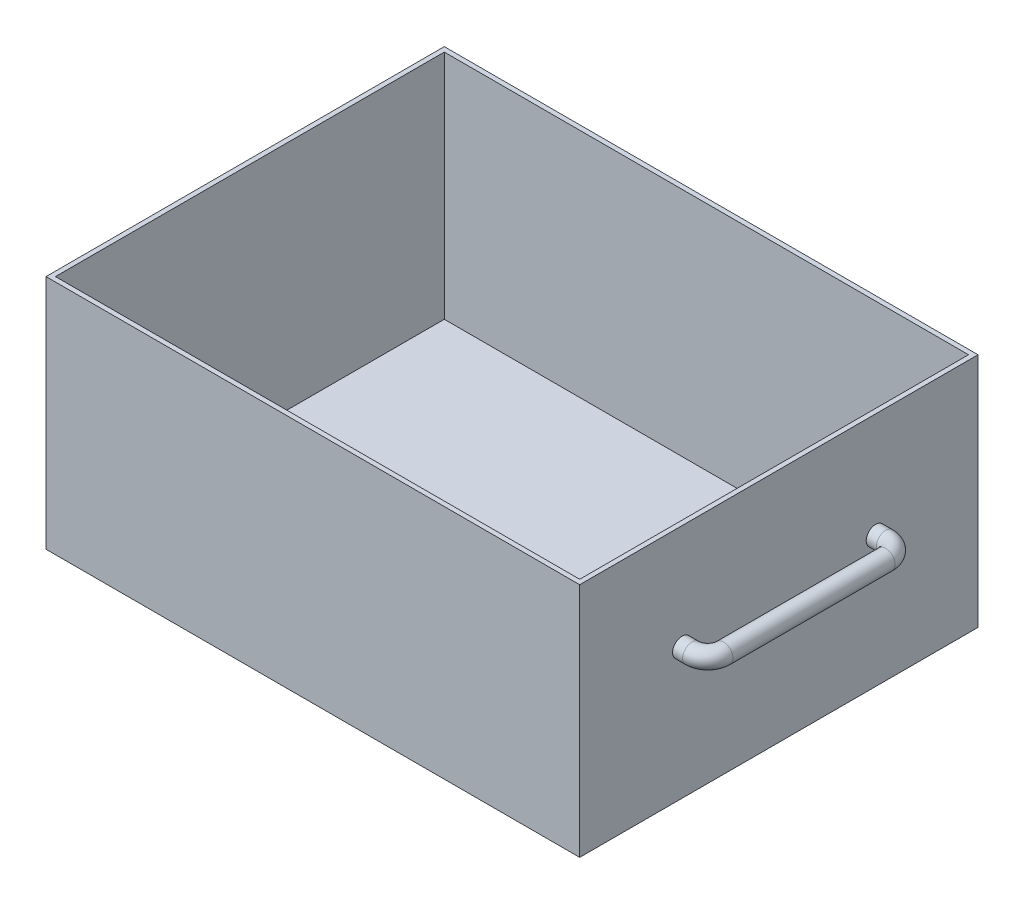
SolidWorks part; units mm, degrees
ref_plane "前视" through (0, 0, 0) normal (0, 0, 1) x (1, 0, 0)
ref_plane "上视" through (0, 0, 0) normal (0, 1, 0) x (1, 0, 0)
ref_plane "右视" through (0, 0, 0) normal (1, 0, 0) x (0, 0, -1)
sketch "Sketch1" plane through (0, 0, 0) normal (0, 1, 0) x (1, 0, 0)
  line L1 (-175.8201, 119.8745) -> (163.1799, 119.8745)
  line L2 (-175.8201, 119.8745) -> (-175.8201, -133.1255)
  line L3 (-175.8201, -133.1255) -> (163.1799, -133.1255)
  line L4 (163.1799, 119.8745) -> (163.1799, -133.1255)
  dimension "D1" = 339
  dimension "D2" = 253
  dimension "D3" = 163.1799
extrude "Boss-Extrude1" add sketch "Sketch1" along normal blind 150
shell "Shell1" thickness 3
sketch "Sketch2" plane through (163.1799, 0, 0) normal (1, 0, 0) x (0, 0, -1)
  line L1 (-133.1255, 150) -> (-133.1255, 0) construction
  circle A0 centre (-68.1255, 83.1724) radius 6
  point P9 (54.8745, 83.1724)
  dimension "D2" = 65
ref_plane "Plane1" through (0, 83.1724, 0) normal (0, 1, 0) x (1, 0, 0)
sketch "Sketch4" plane through (0, 83.1724, 0) normal (0, 1, 0) x (1, 0, 0)
  line L0 (163.1799, -68.1255) -> (169.5656, -68.1255)
  line L1 (179.5656, -58.1255) -> (179.5656, 44.8745)
  line L2 (169.5656, 54.8745) -> (163.1799, 54.8745)
  arc A0 (179.5656, -58.1255) -> (169.5656, -68.1255) centre (169.5656, -58.1255) cw
  arc A1 (179.5656, 44.8745) -> (169.5656, 54.8745) centre (169.5656, 44.8745) ccw
  dimension "D1" = 10
sweep "Sweep2" add profiles "Sketch2" path "Sketch4"
